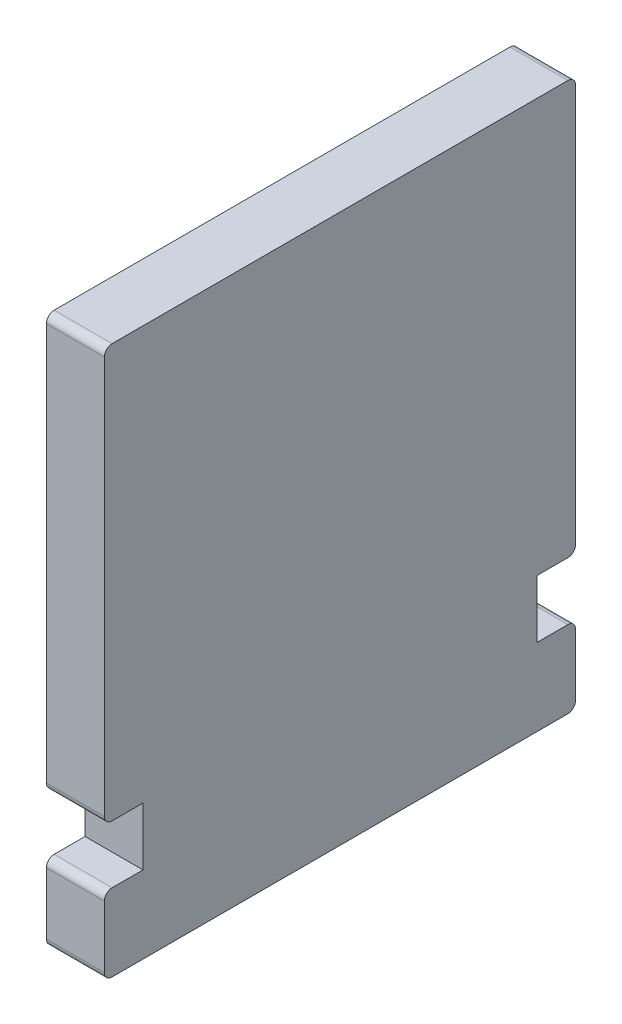
SolidWorks part; units mm, degrees
ref_plane "前视基准面" through (0, 0, 0) normal (0, 0, 1) x (1, 0, 0)
ref_plane "上视基准面" through (0, 0, 0) normal (0, 1, 0) x (1, 0, 0)
ref_plane "右视基准面" through (0, 0, 0) normal (1, 0, 0) x (0, 0, -1)
sketch "草图1" plane through (0, 0, 0) normal (0, 0, 1) x (1, 0, 0)
  line L1 (0, 0) -> (1.5, 0)
  line L2 (0, 0) -> (0, 14.2)
  line L3 (0, 14.2) -> (1.5, 14.2)
  line L4 (1.5, 0) -> (1.5, 14.2)
  point P5 (0.75, 0)
  dimension "D1" = 1.5
  dimension "D2" = 14.2
extrude "凸台-拉伸1" add sketch "草图1" along normal blind 12.2
sketch "草图5" plane through (1.5, 0, 0) normal (1, 0, 0) x (0, 0, -1)
  line L0 (-12.2, 0) -> (0, 0) construction
  line L1 (-13.7975, 3.5) -> (-11.2, 3.5)
  line L2 (-13.7975, 3.5) -> (-13.7975, 2)
  line L3 (-13.7975, 2) -> (-11.2, 2)
  line L4 (-11.2, 3.5) -> (-11.2, 2)
  line L5 (-1, 3.5) -> (1.6553, 3.5)
  line L6 (-1, 3.5) -> (-1, 2)
  line L7 (-1, 2) -> (1.6553, 2)
  line L8 (1.6553, 3.5) -> (1.6553, 2)
  line L9 (-12.2, 0) -> (-12.2, 14.2) construction
  line L10 (0, 0) -> (0, 14.2) construction
  point P10 (-11.2, 2.75)
  point P13 (-1, 2.75)
  dimension "D1" = 2
  dimension "D2" = 2
  dimension "D3" = 1.5
  dimension "D4" = 1.5
  dimension "D5" = 1
  dimension "D6" = 1
extrude "切除-拉伸2" cut sketch "草图5" against normal up to next
fillet "圆角1" radius 0.2 8 edges at (0.75, 14.2, 0) (0.75, 3.5, 0) (0.75, 2, 0) (0.75, 0, 0) (0.75, 14.2, 12.2) (0.75, 2, 12.2) (0.75, 3.5, 12.2) (0.75, 0, 12.2)
